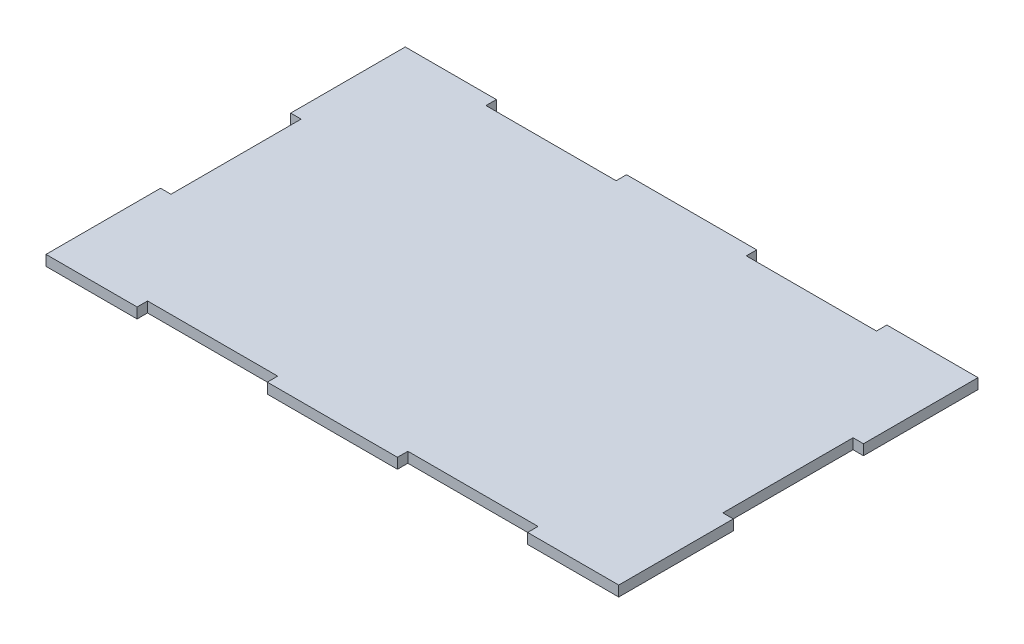
SolidWorks part; units mm, degrees
ref_plane "Front Plane" through (0, 0, 0) normal (0, 0, 1) x (1, 0, 0)
ref_plane "Top Plane" through (0, 0, 0) normal (0, 1, 0) x (1, 0, 0)
ref_plane "Right Plane" through (0, 0, 0) normal (1, 0, 0) x (0, 0, -1)
sketch "Sketch2" plane through (0, 0, 0) normal (0, 1, 0) x (1, 0, 0)
  line L0 (-110, 69) -> (-110, 25)
  line L1 (-110, -69) -> (-75, -69)
  line L2 (110, -69) -> (110, -25)
  line L3 (110, 69) -> (75, 69)
  line L4 (-75, 69) -> (-75, 65)
  line L5 (-75, 65) -> (-25, 65)
  line L6 (-25, 65) -> (-25, 69)
  line L7 (25, 69) -> (25, 65)
  line L8 (25, 65) -> (75, 65)
  line L9 (75, 65) -> (75, 69)
  line L10 (-75, 69) -> (-110, 69)
  line L11 (25, 69) -> (-25, 69)
  line L12 (-75, -69) -> (-75, -65)
  line L13 (-75, -65) -> (-25, -65)
  line L14 (-25, -65) -> (-25, -69)
  line L15 (25, -69) -> (25, -65)
  line L16 (25, -65) -> (75, -65)
  line L17 (75, -65) -> (75, -69)
  line L18 (-25, -69) -> (25, -69)
  line L19 (75, -69) -> (110, -69)
  line L20 (-110, 25) -> (-106, 25)
  line L21 (-106, 25) -> (-106, -25)
  line L22 (-106, -25) -> (-110, -25)
  line L23 (-110, -25) -> (-110, -69)
  line L24 (110, 25) -> (106, 25)
  line L25 (106, 25) -> (106, -25)
  line L26 (106, -25) -> (110, -25)
  line L27 (110, 25) -> (110, 69)
  dimension "D1" = 220
  dimension "D3" = 50
  dimension "D4" = 50
  dimension "D5" = 50
  dimension "D6" = 4
  dimension "D7" = 4
  dimension "D8" = 25
  dimension "D9" = 69
  dimension "D10" = 110
  dimension "D11" = 50
  dimension "D12" = 50
  dimension "D13" = 50
  dimension "D14" = 4
  dimension "D15" = 4
  dimension "D16" = 25
  dimension "D17" = 50
  dimension "D18" = 4
  dimension "D19" = 25
  dimension "D20" = 50
  dimension "D21" = 25
  dimension "D22" = 4
  dimension "D23" = 69
extrude "Boss-Extrude1" add sketch "Sketch2" along normal blind 4
